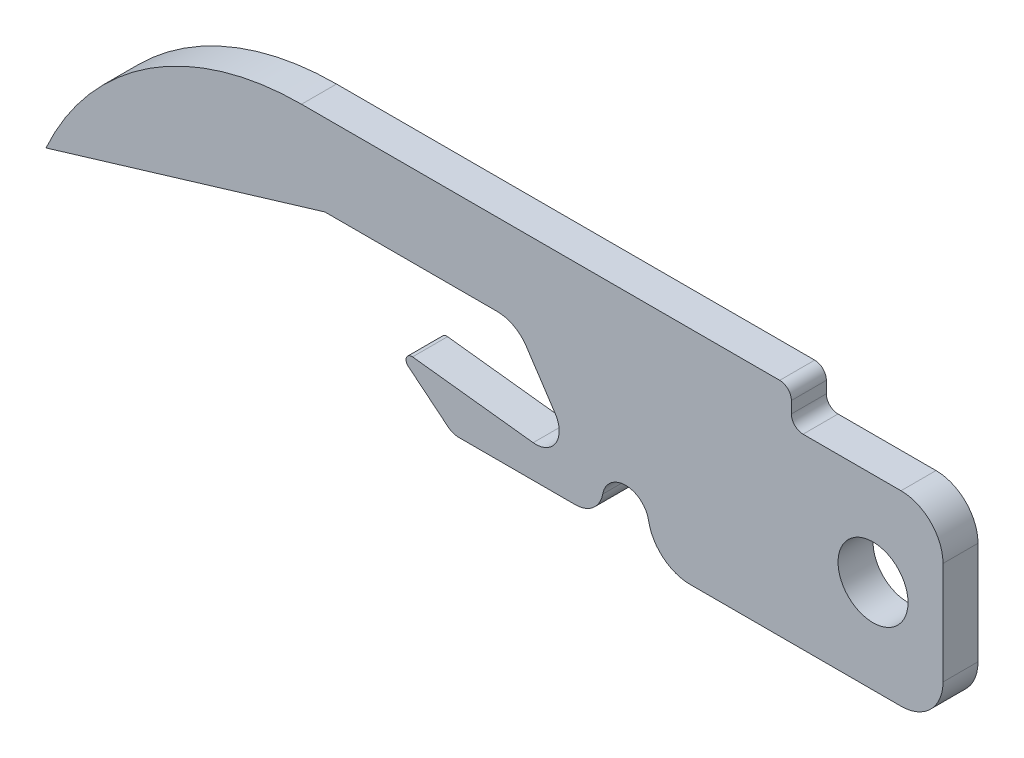
SolidWorks part; units mm, degrees
ref_plane "Front Plane" through (0, 0, 0) normal (0, 0, 1) x (1, 0, 0)
ref_plane "Top Plane" through (0, 0, 0) normal (0, 1, 0) x (1, 0, 0)
ref_plane "Right Plane" through (0, 0, 0) normal (1, 0, 0) x (0, 0, -1)
sketch "Sketch1" plane through (0, 0, 0) normal (0, 0, 1) x (1, 0, 0)
  line L2 (10.954, 9.5) -> (31.454, 9.5)
  line L3 (31.954, 9) -> (31.954, 8.5)
  line L4 (32.454, 8) -> (38.454, 8)
  line L5 (38.454, 8) -> (38.454, 0)
  line L6 (38.454, 0) -> (27.6113, 0)
  line L9 (0, 2.4) -> (11.954, 6)
  line L11 (11.954, 6) -> (19.3426, 6)
  line L15 (22.6874, 0.5) -> (17.7054, 0.5)
  line L18 (20.5952, 5.3253) -> (21.835, 3.4435)
  line L19 (20.8848, 1.9) -> (15.7131, 2.5)
  line L20 (17.2317, 0.6685) -> (15.5264, 2.0578)
  arc A2 (32.454, 8) -> (31.954, 8.5) centre (32.454, 8.5) cw
  arc A3 (31.954, 9) -> (31.454, 9.5) centre (31.454, 9) ccw
  circle A6 centre (35.454, 4) radius 1.5
  arc A7 (10.954, 9.5) -> (0, 2.4) centre (10.954, -2.5) ccw
  arc A8 (19.3426, 6) -> (20.5952, 5.3253) centre (19.3426, 4.5) cw
  arc A9 (27.6113, 0) -> (25.8326, 1.4811) centre (27.6113, 1.8087) cw
  arc A10 (25.8326, 1.4811) -> (23.8656, 1.4811) centre (24.8491, 1.3) ccw
  arc A11 (17.7054, 0.5) -> (17.2317, 0.6685) centre (17.7054, 1.25) cw
  arc A14 (22.6874, 0.5) -> (23.8656, 1.4811) centre (22.6874, 1.6981) ccw
  arc A15 (21.835, 3.4435) -> (20.8848, 1.9) centre (21, 2.8933) cw
  arc A16 (15.7131, 2.5) -> (15.5264, 2.0578) centre (15.6843, 2.2517) ccw
  point P15 (35.454, 8)
  point P18 (31.954, 8)
  point P22 (31.954, 9.5)
  point P36 (0, 0)
  point P37 (28.2567, 2.7497)
  point P38 (28.1816, 2.4709)
  point P39 (31.2741, 4.5)
  point P40 (23.454, 0.7774)
  point P41 (26.454, 0.4188)
  point P42 (24.0959, 5.967)
  point P43 (30.5805, 1.9979)
  point P44 (17.454, 0.5434)
  point P45 (25.3488, 6)
  point P46 (31.7865, 6)
  point P47 (29.5, 6)
  point P49 (32.0356, 3.0748)
  point P50 (29.9539, 6)
  point P51 (31.2843, 1.7814)
  point P52 (0, 0)
  point P53 (0, 0)
  point P54 (32.1665, 1.955)
  point P55 (28.2091, 2.4)
  point P56 (28.2091, 2.4)
  point P57 (28.2091, 2.4594)
  point P58 (28.2091, 2.4)
  point P59 (32.3321, 2.2102)
  point P60 (0, 0)
  point P61 (0, 0)
  point P62 (15.454, 2.3489)
  point P63 (0, 0)
  point P64 (19.2861, 1.7893)
  point P65 (20.6382, 4.8436)
  point P66 (0, 0)
  point P67 (0, 0)
  point P68 (21.0636, 2.5)
  point P69 (20.054, 5.8206)
  point P70 (0, 0)
  dimension "D11" = 0.5
  dimension "D12" = 3
  dimension "D13" = 0.5
  dimension "D7" = 27.5
  dimension "D8" = 4
  dimension "D2" = 3
  dimension "D16" = 1
  dimension "D9" = 3.6
  dimension "D15" = 1.5
  dimension "D17" = 0.25
  dimension "D19" = 1
  dimension "D23" = 0.75
  dimension "D24" = 12
  dimension "D25" = 2
  dimension "D3" = 1.5
  dimension "D4" = 12
  dimension "D5" = 8
  dimension "D6" = 6.5
  dimension "D10" = 3.5
  dimension "D14" = 9
  dimension "D18" = 11.5
  dimension "D20" = 11
  dimension "D21" = 0.6
  dimension "D22" = 3.4
  dimension "D26" = 8.2
  dimension "D27" = 21
extrude "Boss-Extrude1" add sketch "Sketch1" along normal mid plane 1.5
fillet "Fillet1" radius 1.8 2 edges at (38.454, 0, 0) (38.454, 8, 0)
